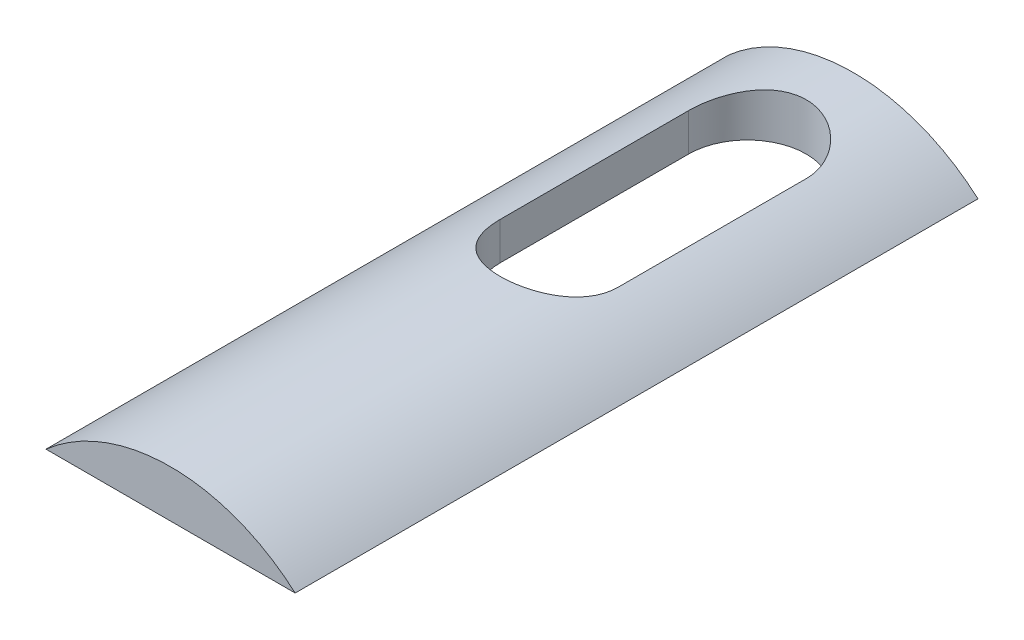
SolidWorks part; units mm, degrees
ref_plane "Front" through (0, 0, 0) normal (0, 0, 1) x (1, 0, 0)
ref_plane "Top" through (0, 0, 0) normal (0, 1, 0) x (1, 0, 0)
ref_plane "Right" through (0, 0, 0) normal (1, 0, 0) x (0, 0, -1)
sketch "Sketch1" plane through (0, 0, 0) normal (0, 0, 1) x (1, 0, 0)
  line L0 (-2.6458, 0) -> (2.6458, 0)
  line L1 (0, 0) -> (0, 1) construction
  arc A0 (2.6458, 0) -> (-2.6458, 0) centre (0, -3) ccw
  dimension "D1" = 8
  dimension "D2" = 1
extrude "Boss-Extrude1" add sketch "Sketch1" along normal blind 14.5
sketch "Sketch2" plane through (0, 0, 0) normal (0, -1, 0) x (1, 0, 0)
  line L0 (0, 2.25) -> (0, 6.25) construction
  line L1 (-1.25, 2.25) -> (-1.25, 6.25)
  line L2 (1.25, 2.25) -> (1.25, 6.25)
  arc A1 (-1.25, 2.25) -> (1.25, 2.25) centre (0, 2.25) ccw
  arc A2 (1.25, 6.25) -> (-1.25, 6.25) centre (0, 6.25) ccw
  point P2 (0, 4.25)
  point P8 (0, 1)
  dimension "D2" = 1.25
  dimension "D1" = 4
  dimension "D3" = 1
extrude "Cut-Extrude1" cut sketch "Sketch2" against normal through all
